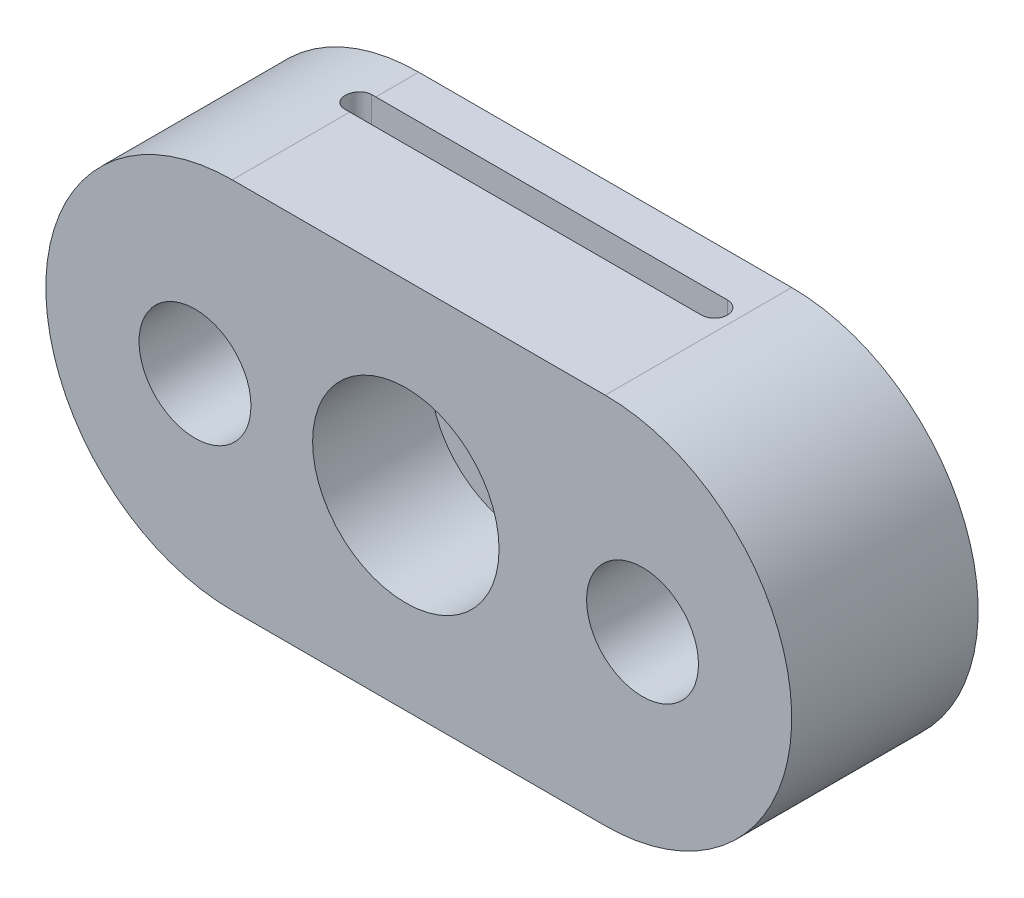
SolidWorks part; units mm, degrees
ref_plane "Front Plane" through (0, 0, 0) normal (0, 0, 1) x (1, 0, 0)
ref_plane "Top Plane" through (0, 0, 0) normal (0, 1, 0) x (1, 0, 0)
ref_plane "Right Plane" through (0, 0, 0) normal (1, 0, 0) x (0, 0, -1)
sketch "Sketch12" plane through (0, 0, 0) normal (0, 0, 1) x (1, 0, 0)
  line L0 (-9.3064, 0) -> (10.6936, 0) construction
  line L1 (-9.3064, 10) -> (10.6936, 10)
  line L2 (-9.3064, -10) -> (10.6936, -10)
  line L3 (-19.3064, 9.5905) -> (-19.3064, -10.9748)
  line L4 (20.6936, 7.8913) -> (20.6936, -9.0795)
  arc A0 (-9.3064, 10) -> (-9.3064, -10) centre (-9.3064, 0) ccw
  arc A1 (10.6936, -10) -> (10.6936, 10) centre (10.6936, 0) ccw
  circle A2 centre (-11.3064, 0) radius 3
  circle A3 centre (0, 0) radius 5
  circle A4 centre (12.6936, 0) radius 3
  point P3 (0.6936, 0)
  point P16 (-19.3064, -0.6921)
  point P19 (20.6936, -0.5941)
  dimension "D2" = 10
  dimension "D3" = 8
  dimension "D4" = 6
  dimension "D5" = 10
  dimension "D6" = 6
  dimension "D7" = 8
  dimension "D1" = 20
extrude "Boss-Extrude1" add sketch "Sketch12" along normal blind 7
sketch "Sketch13" plane through (0, 0, 0) normal (0, 0, -1) x (-1, 0, 0)
  line L0 (-10.6936, 10) -> (9.3064, 10)
  line L1 (-10.6936, -10) -> (9.3064, -10)
  arc A0 (-10.6936, -10) -> (-10.6936, 10) centre (-10.6936, 0) cw
  arc A1 (9.3064, -10) -> (9.3064, 10) centre (9.3064, 0) ccw
extrude "Boss-Extrude2" add sketch "Sketch13" along normal blind 3
ref_plane "Plane3" through (0, -10, 0) normal (0, -1, 0) x (-1, 0, 0)
sketch "Sketch15" plane through (0, -10, 0) normal (0, -1, 0) x (-1, 0, 0)
  line L0 (0, 14.4342) -> (0, -12.6959) construction
  line L1 (-28.7512, 0) -> (26.1921, 0) construction
  line L3 (-9.55, 0.7) -> (9.55, 0.7)
  line L5 (-9.55, -0.7) -> (9.55, -0.7)
  arc A0 (-9.55, 0.7) -> (-9.55, -0.7) centre (-9.55, 0) ccw
  arc A2 (9.55, -0.7) -> (9.55, 0.7) centre (9.55, 0) ccw
  dimension "D2" = 0.7
  dimension "D1" = 19.1
extrude "Cut-Extrude1" cut sketch "Sketch15" against normal blind 30
sketch "Sketch16" plane through (0, 0, -3) normal (0, 0, -1) x (-1, 0, 0)
  line L5 (-10.6936, 10) -> (9.3064, 10)
  line L6 (-10.6936, -10) -> (9.3064, -10)
  arc A2 (9.3064, -10) -> (9.3064, 10) centre (9.3064, 0) ccw
  arc A3 (-10.6936, -10) -> (-10.6936, 10) centre (-10.6936, 0) cw
extrude "Boss-Extrude3" add sketch "Sketch16" along normal blind 5 draft 70
